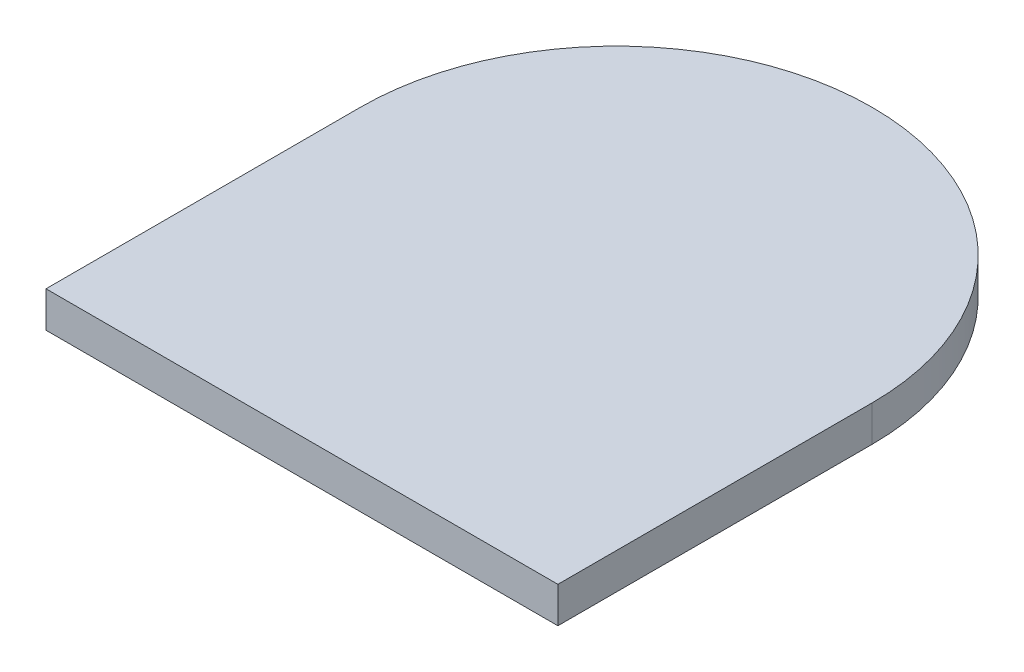
SolidWorks part; units mm, degrees
ref_plane "前视基准面" through (0, 0, 0) normal (0, 0, 1) x (1, 0, 0)
ref_plane "上视基准面" through (0, 0, 0) normal (0, 1, 0) x (1, 0, 0)
ref_plane "右视基准面" through (0, 0, 0) normal (1, 0, 0) x (0, 0, -1)
other "Configuration Table"
sketch "草图1" plane through (0, 0, 0) normal (0, 1, 0) x (1, 0, 0)
  line L0 (-28.5, 0) -> (-28.5, -35)
  line L1 (-28.5, -35) -> (28.5, -35)
  line L2 (28.5, -35) -> (28.5, 0)
  arc A0 (28.5, 0) -> (-28.5, 0) centre (0, 0) ccw
  dimension "D1" = 57
  dimension "D2" = 35
extrude "凸台-拉伸1" add sketch "草图1" along normal blind 4
